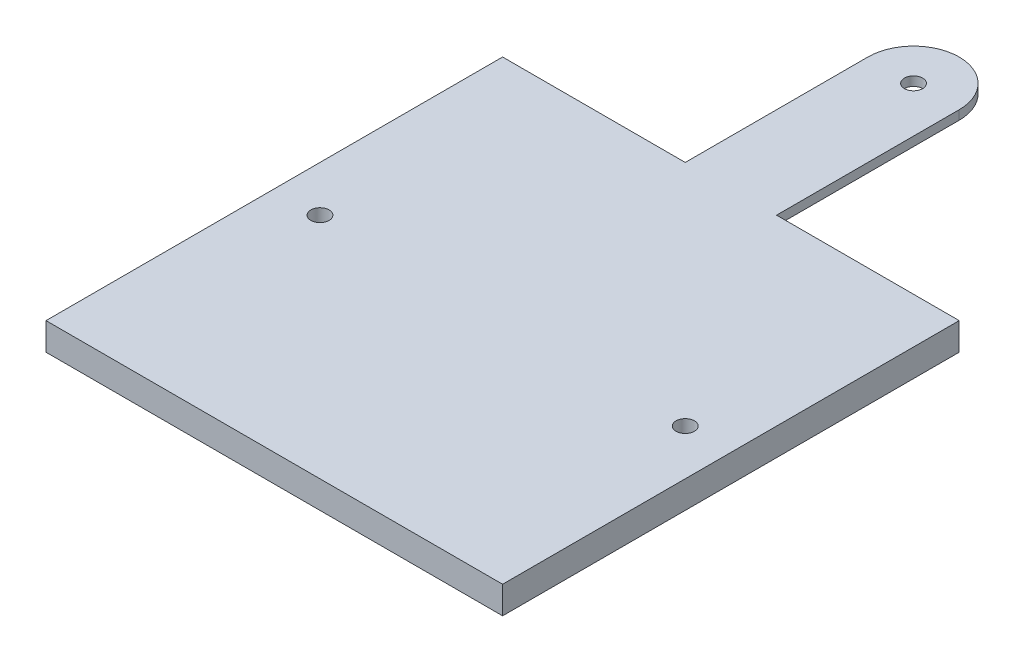
SolidWorks part; units mm, degrees
ref_plane "Front Plane" through (0, 0, 0) normal (0, 0, 1) x (1, 0, 0)
ref_plane "Top Plane" through (0, 0, 0) normal (0, 1, 0) x (1, 0, 0)
ref_plane "Right Plane" through (0, 0, 0) normal (1, 0, 0) x (0, 0, -1)
sketch "Sketch1" plane through (0, 0, 0) normal (0, 1, 0) x (1, 0, 0)
  line L0 (-50, 0) -> (-50, -200)
  line L1 (50, 0) -> (50, -200)
  line L2 (50, -200) -> (250, -200)
  line L3 (250, -200) -> (250, -700)
  line L4 (250, -700) -> (-250, -700)
  line L5 (-250, -700) -> (-250, -200)
  line L6 (-250, -200) -> (-50, -200)
  arc A0 (50, 0) -> (-50, 0) centre (0, 0) ccw
  circle A1 centre (0, 0) radius 10
  dimension "D1" = 20
  dimension "D2" = 100
  dimension "D3" = 500
  dimension "D4" = 200
  dimension "D5" = 500
  dimension "D6" = 200
  dimension "D7" = 200
extrude "Boss-Extrude1" add sketch "Sketch1" along normal blind 10
sketch "Sketch2" plane through (0, 0, 0) normal (0, -1, 0) x (1, 0, 0)
  line L1 (-250, 700) -> (250, 700)
  line L2 (-250, 700) -> (-250, 200)
  line L3 (-250, 200) -> (250, 200)
  line L4 (250, 700) -> (250, 200)
extrude "Boss-Extrude2" add sketch "Sketch2" along normal blind 20
sketch "Sketch3" plane through (0, 10, 0) normal (0, 1, 0) x (1, 0, 0)
  line L0 (-250, -450) -> (250, -450) construction
  line L1 (-250, -200) -> (-250, -700) construction
  line L2 (250, -700) -> (250, -200) construction
  line L3 (0, 0) -> (0, -700) construction
  line L4 (-250, -700) -> (250, -700) construction
  circle A0 centre (200, -450) radius 10
  circle A1 centre (-200, -450) radius 10
  dimension "D1" = 20
  dimension "D2" = 50
extrude "Cut-Extrude1" cut sketch "Sketch3" against normal through all
